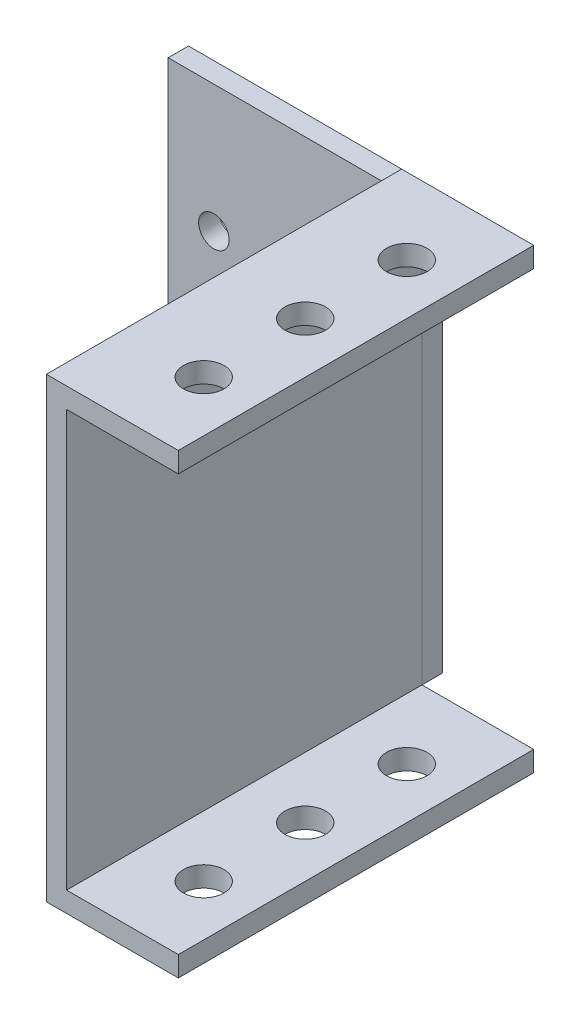
SolidWorks part; units mm, degrees
material "AISI 304"
ref_plane "前视基准面" through (0, 0, 0) normal (0, 0, 1) x (1, 0, 0)
ref_plane "上视基准面" through (0, 0, 0) normal (0, 1, 0) x (1, 0, 0)
ref_plane "右视基准面" through (0, 0, 0) normal (1, 0, 0) x (0, 0, -1)
sketch "Sketch1" plane through (0, 0, 0) normal (0, 0, 1) x (1, 0, 0)
  line L0 (0, 0) -> (0, 45)
  line L1 (0, 45) -> (13, 45)
  line L2 (13, 45) -> (13, 43)
  line L3 (13, 43) -> (2, 43)
  line L4 (2, 43) -> (2, 2)
  line L5 (2, 2) -> (13, 2)
  line L6 (13, 2) -> (13, 0)
  line L7 (13, 0) -> (0, 0)
  point P6 (13, 1)
  dimension "D1" = 45
  dimension "D2" = 2
  dimension "D3" = 2
  dimension "D4" = 2
  dimension "D5" = 13
  dimension "D6" = 13
extrude "Boss-Extrude1" add sketch "Sketch1" along normal blind 35
sketch "Sketch2" plane through (0, 0, 0) normal (0, 0, -1) x (-1, 0, 0)
  line L7 (0, 0) -> (-13, 0) construction
  line L8 (-2, 43) -> (23, 43)
  line L9 (-2, 43) -> (-2, 2)
  line L10 (-2, 2) -> (23, 2)
  line L11 (23, 43) -> (23, 2)
  dimension "D1" = 2
  dimension "D2" = 25
extrude "Boss-Extrude2" add sketch "Sketch2" along normal blind 2 separate body
sketch "Sketch3" plane through (0, 0, -2) normal (0, 0, -1) x (-1, 0, 0)
  line L3 (18.5, 30.45) -> (18.5, 14.45) construction
  line L4 (18.5, 30.45) -> (3.5, 30.45) construction
  line L5 (23, 2) -> (23, 43) construction
  line L6 (3.5, 14.45) -> (18.5, 14.45) construction
  line L7 (23, 43) -> (-2, 43) construction
  circle A0 centre (18.5, 30.45) radius 1.5
  circle A1 centre (3.5, 30.45) radius 1.5
  circle A2 centre (18.5, 14.45) radius 1.5
  circle A3 centre (3.5, 14.45) radius 1.5
  dimension "D4" = 3
  dimension "D5" = 3
  dimension "D9" = 3
  dimension "D10" = 3
  dimension "D2" = 15
  dimension "D3" = 16
  dimension "D6" = 16
  dimension "D7" = 4.5
  dimension "D8" = 15
  dimension "D11" = 12.55
extrude "Cut-Extrude1" cut sketch "Sketch3" against normal blind 2
sketch "Sketch4" plane through (0, 45, 0) normal (0, 1, 0) x (1, 0, 0)
  line L0 (8, -35) -> (8, 0) construction
  line L1 (13, -35) -> (0, -35) construction
  line L2 (13, 0) -> (0, 0) construction
  line L3 (13, -35) -> (13, 0) construction
  circle A0 centre (8, -17.5) radius 2
  circle A1 centre (8, -27.5) radius 2
  circle A2 centre (8, -7.5) radius 2
  dimension "D3" = 4
  dimension "D4" = 4
  dimension "D6" = 4
  dimension "D1" = 5
  dimension "D2" = 10
  dimension "D5" = 10
extrude "Cut-Extrude2" cut sketch "Sketch4" against normal through all
